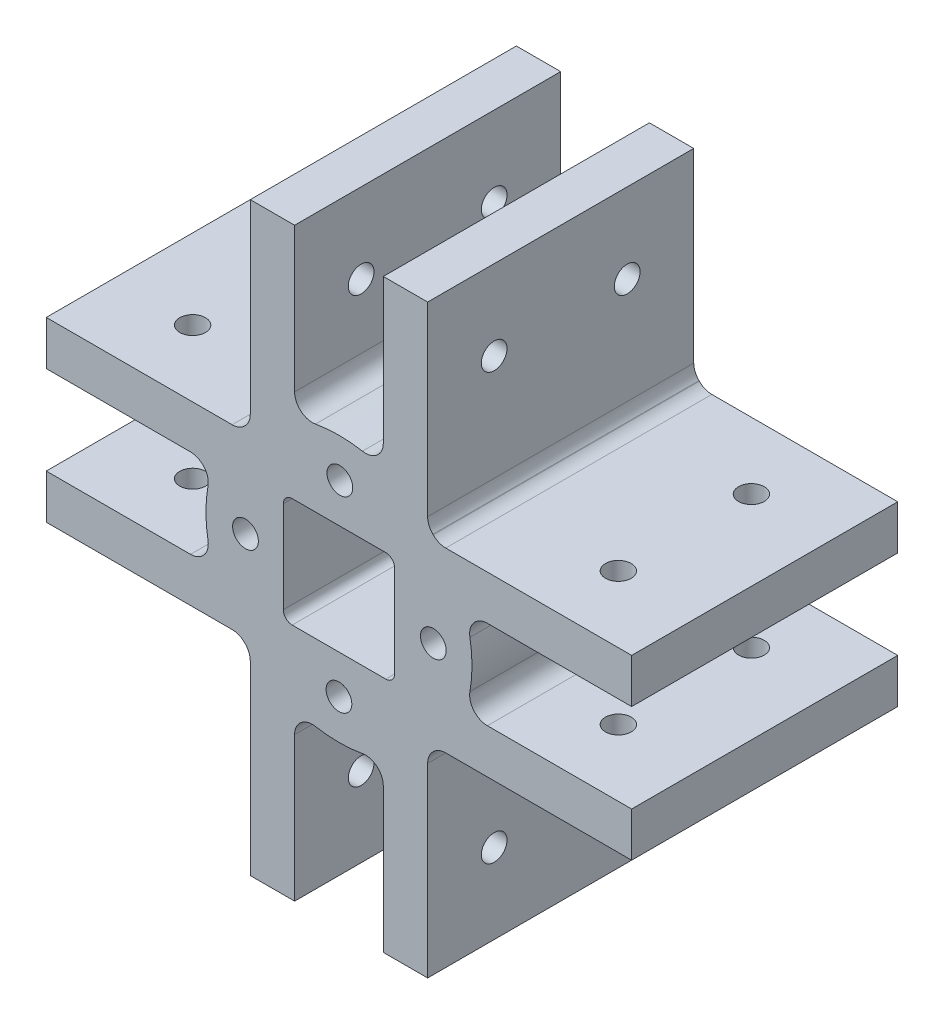
SolidWorks part; units mm, degrees
ref_plane "Front Plane" through (0, 0, 0) normal (0, 0, 1) x (1, 0, 0)
ref_plane "Top Plane" through (0, 0, 0) normal (0, 1, 0) x (1, 0, 0)
ref_plane "Right Plane" through (0, 0, 0) normal (1, 0, 0) x (0, 0, -1)
sketch "Sketch1" plane through (0, 0, 0) normal (0, 0, 1) x (1, 0, 0)
  circle A0 centre (0, 0) radius 15
  dimension "D2" = 30
extrude "Boss-Extrude1" add sketch "Sketch1" along normal mid plane 30
sketch "Sketch4" plane through (0, 0, 15) normal (0, 0, 1) x (1, 0, 0)
  line L0 (16.5, 0) -> (-16.5, 0) construction
  line L2 (-10, 0) -> (-5, 0)
  line L3 (0, 0) -> (0, 15.8331) construction
  line L4 (-10, 0) -> (-10, 33)
  line L5 (-10, 33) -> (-5, 33)
  line L6 (-5, 0) -> (-5, 33)
  line L7 (0, -16.5) -> (0, 16.5) construction
  line L8 (10, 33) -> (5, 33)
  line L9 (5, 0) -> (5, 33)
  line L10 (10, 0) -> (5, 0)
  line L11 (10, 0) -> (10, 33)
  dimension "D1" = 33
  dimension "D3" = 5
  dimension "D2" = 5
extrude "Boss-Extrude3" add sketch "Sketch4" against normal up to surface (30 mm away) up to face at (15, 0, -15)
fillet "Fillet2" radius 2 4 edges at (10, 11.1803, 0) (5, 14.1421, 0) (-5, 14.1421, 0) (-10, 11.1803, 0)
pattern_circular "CirPattern7" count 4 over 360 about axis through (0, 0, 0) along (0, 0, 1) of "Boss-Extrude3", "Fillet2"
sketch "Sketch7" plane through (-10, 0, 0) normal (-1, 0, 0) x (0, 0, 1)
  line L0 (-15, 33) -> (15, 33) construction
  line L1 (-15, 12.0416) -> (-15, 33) construction
  circle A0 centre (-7.5, 24) radius 1.45
  circle A1 centre (7.5, 24) radius 1.45
  circle A2 centre (22.5, 24) radius 1.45
  circle A3 centre (37.5, 24) radius 1.45
  circle A4 centre (52.5, 24) radius 1.45
  dimension "D1" = 2.9
  dimension "D2" = 9
  dimension "D3" = 7.5
  dimension "D4" = 5
extrude "Cut-Extrude2" cut sketch "Sketch7" against normal blind 27
pattern_circular "CirPattern9" count 4 over 360 of "Cut-Extrude2"
sketch "Sketch8" plane through (0, 0, 15) normal (0, 0, 1) x (1, 0, 0)
  line L2 (-6.275, 6.175) -> (6.275, 6.175)
  line L3 (-6.275, 6.175) -> (-6.275, -6.175)
  line L4 (-6.275, -6.175) -> (6.275, -6.175)
  line L5 (6.275, 6.175) -> (6.275, -6.175)
  line L6 (-6.275, 6.175) -> (6.275, -6.175) construction
  line L7 (-6.275, -6.175) -> (6.275, 6.175) construction
  point P5 (0, 0)
  point P14 (0, 0)
  dimension "D1" = 12.55
  dimension "D2" = 12.35
extrude "Cut-Extrude3" cut sketch "Sketch8" against normal up to next
sketch "Sketch9" plane through (0, 0, 15) normal (0, 0, 1) x (1, 0, 0)
  line L0 (16.5, 0) -> (-16.5, 0) construction
  line L1 (6.275, -6.175) -> (6.275, 6.175) construction
  circle A0 centre (10.6375, 0) radius 1.45
  circle A1 centre (0, -10.5375) radius 1.45
  circle A2 centre (-10.5375, 0.1) radius 1.45
  circle A3 centre (0.1, 10.6375) radius 1.45
  point P14 (0.05, 0.05)
  dimension "D1" = 2.9
  dimension "D2" = 4.3625
  dimension "D3" = 4
extrude "Cut-Extrude4" cut sketch "Sketch9" against normal blind 10
fillet "Fillet1" radius 1 4 edges at (-6.275, 6.175, 0) (6.275, 6.175, 0) (6.275, -6.175, 0) (-6.275, -6.175, 0)
mirror "Mirror1" about plane through (0, 0, 0) normal (0, 0, 1) of "Cut-Extrude4"
equation "\"drumDiameter\"= 30"
equation "\"D2@Sketch1\"=\"drumDiameter\""
equation "\"drumLength\"= 30"
equation "\"D1@Sketch4\"=\"drumDiameter\"*(0.5+\"drumAbove\")"
equation "\"foamThickness\"= 10"
equation "\"D3@Sketch4\"=\"foamThickness\"/2"
equation "\"drumAbove\"= 0.6"
equation "\"D2@Sketch7\"=\"drumDiameter\"*\"drumAbove\"/2"
equation "\"holderThicc\" = 5"
equation "\"D2@Sketch4\"=\"holderThicc\""
equation "\"D1@Boss-Extrude1\"=\"drumLength\""
equation "\"squareBarLength\"= 12.55"
equation "\"D1@Sketch8\"=\"squareBarLength\""
equation "\"D2@Sketch9\"=(\"drumDiameter\"/2-\"squareBarLength\"/2)/2"
equation "\"squareBarShortLen\"= 12.35"
equation "\"D2@Sketch8\"=\"squareBarShortLen\""
